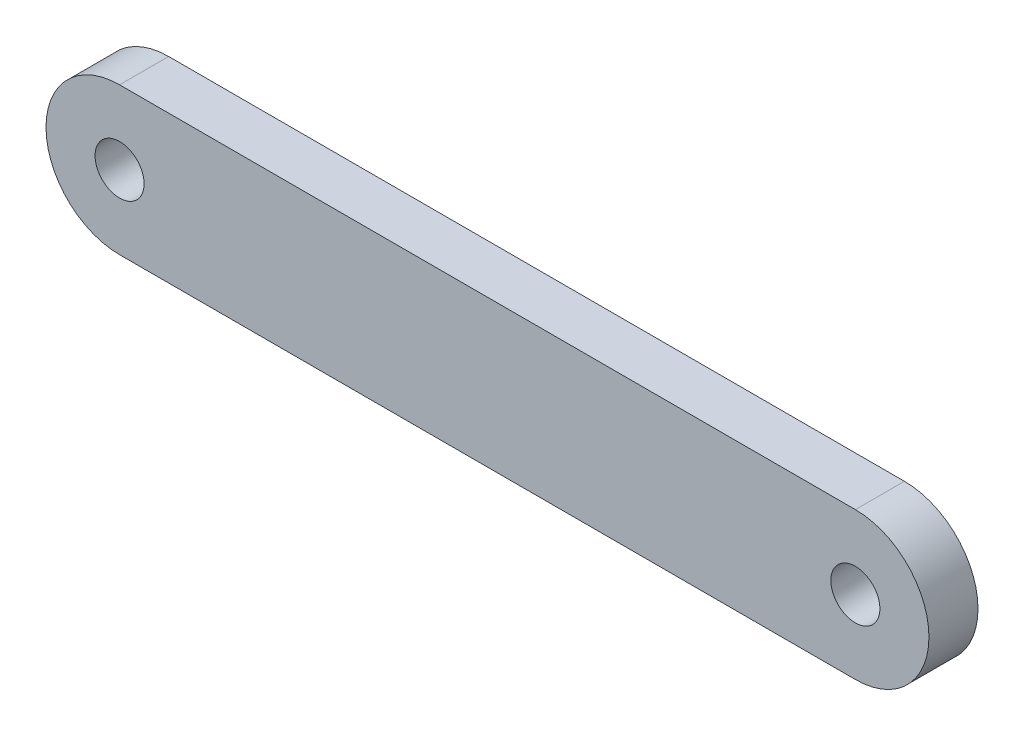
SolidWorks part; units mm, degrees
ref_plane "Ön Düzlem" through (0, 0, 0) normal (0, 0, 1) x (1, 0, 0)
ref_plane "Üst Düzlem" through (0, 0, 0) normal (0, 1, 0) x (1, 0, 0)
ref_plane "Sağ Düzlem" through (0, 0, 0) normal (1, 0, 0) x (0, 0, -1)
sketch "Çizim1" plane through (0, 0, 0) normal (0, 0, 1) x (1, 0, 0)
  line L0 (-75, 0) -> (75, 0) construction
  line L1 (-75, 15) -> (75, 15)
  line L2 (-75, -15) -> (75, -15)
  arc A0 (-75, 15) -> (-75, -15) centre (-75, 0) ccw
  arc A1 (75, -15) -> (75, 15) centre (75, 0) ccw
  circle A2 centre (75, 0) radius 5
  circle A3 centre (-75, 0) radius 5
  point P2 (0, 0)
  dimension "D2" = 10
  dimension "D3" = 15
  dimension "D4" = 10
  dimension "D1" = 150
extrude "Yükseklik-Ekstrüzyon1" add sketch "Çizim1" along normal mid plane 10 contours L2 A1 L1 A0
